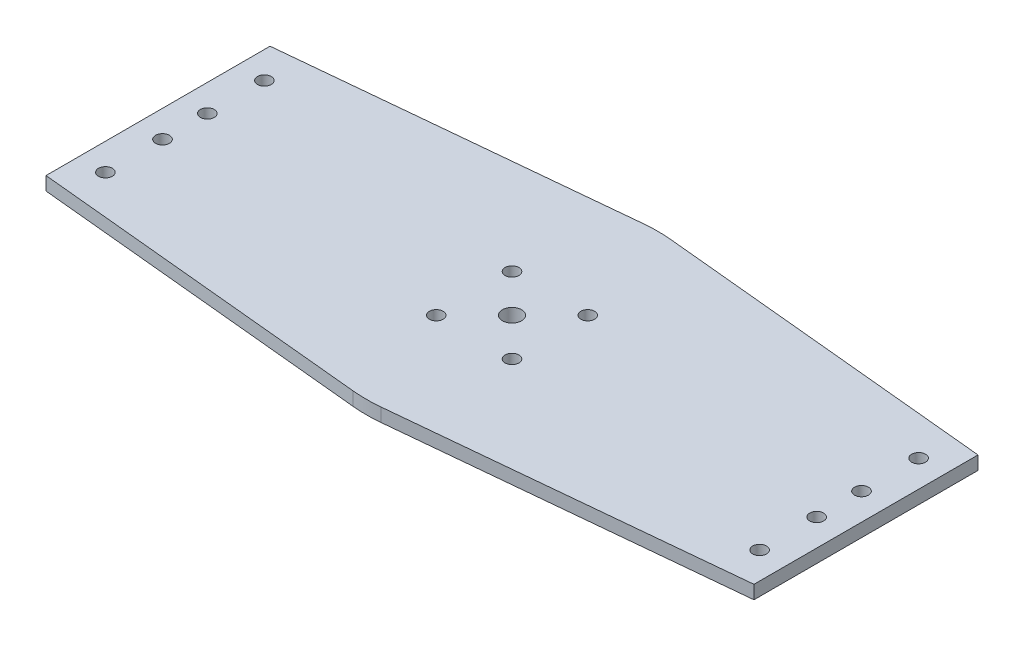
SolidWorks part; units mm, degrees
ref_plane "前视基准面" through (0, 0, 0) normal (0, 0, 1) x (1, 0, 0)
ref_plane "上视基准面" through (0, 0, 0) normal (0, 1, 0) x (1, 0, 0)
ref_plane "右视基准面" through (0, 0, 0) normal (1, 0, 0) x (0, 0, -1)
sketch "草图1" plane through (0, 0, 0) normal (0, 1, 0) x (1, 0, 0)
  line L1 (-79, 25) -> (-79, -25)
  line L2 (79, 25) -> (79, -25)
  line L3 (-79, 25) -> (-3.1334, 32.3486)
  line L4 (79, 25) -> (3.1334, 32.3486)
  line L5 (-79, -25) -> (-3.1334, -32.3486)
  line L6 (79, -25) -> (3.1334, -32.3486)
  arc A0 (-3.1334, -32.3486) -> (3.1334, -32.3486) centre (0, 0) ccw
  arc A1 (3.1334, 32.3486) -> (-3.1334, 32.3486) centre (0, 0) ccw
  point P6 (0, 0)
  point P9 (-79, 0)
  point P12 (79, 0)
  dimension "D1" = 65
  dimension "D2" = 158
  dimension "D3" = 50
  dimension "D4" = 50
  dimension "D5" = 79
  dimension "D6" = 25
  dimension "D7" = 25
extrude "凸台-拉伸1" add sketch "草图1" along normal blind 3
sketch "草图2" plane through (0, 3, 0) normal (0, 1, 0) x (1, 0, 0)
  line L1 (-8.45, 8.45) -> (8.45, 8.45) construction
  line L2 (-8.45, 8.45) -> (-8.45, -8.45) construction
  line L3 (-8.45, -8.45) -> (8.45, -8.45) construction
  line L4 (8.45, 8.45) -> (8.45, -8.45) construction
  line L5 (-8.45, 8.45) -> (8.45, -8.45) construction
  line L6 (-8.45, -8.45) -> (8.45, 8.45) construction
  circle A0 centre (-8.45, 8.45) radius 1.55
  circle A1 centre (8.45, 8.45) radius 1.55
  circle A2 centre (8.45, -8.45) radius 1.55
  circle A3 centre (-8.45, -8.45) radius 1.55
  circle A4 centre (0, 0) radius 2.15
  point P0 (0, 0)
  dimension "D3" = 3.1
  dimension "D4" = 3.1
  dimension "D5" = 3.1
  dimension "D6" = 3.1
  dimension "D7" = 4.3
  dimension "D1" = 16.9
  dimension "D2" = 16.9
extrude "切除-拉伸1" cut sketch "草图2" against normal blind 3
sketch "草图3" plane through (0, 0, 0) normal (0, -1, 0) x (1, 0, 0)
  line L0 (-79, 0) -> (-57.9247, 0) construction
  line L1 (-79, -25) -> (-79, 25) construction
  line L2 (-73, 19.3245) -> (-73, -18.5287) construction
  circle A0 centre (-73, 17.74) radius 1.55
  circle A1 centre (-73, 5) radius 1.55
  circle A2 centre (-73, -5) radius 1.55
  circle A3 centre (-73, -17.74) radius 1.55
  dimension "D2" = 3.1
  dimension "D3" = 3.1
  dimension "D4" = 3.1
  dimension "D5" = 3.1
  dimension "D6" = 12.74
  dimension "D7" = 10
  dimension "D8" = 12.74
  dimension "D9" = 5
  dimension "D1" = 6
extrude "切除-拉伸2" cut sketch "草图3" against normal blind 4
mirror "镜向1" about plane through (0, 0, 0) normal (1, 0, 0) of "切除-拉伸2"
